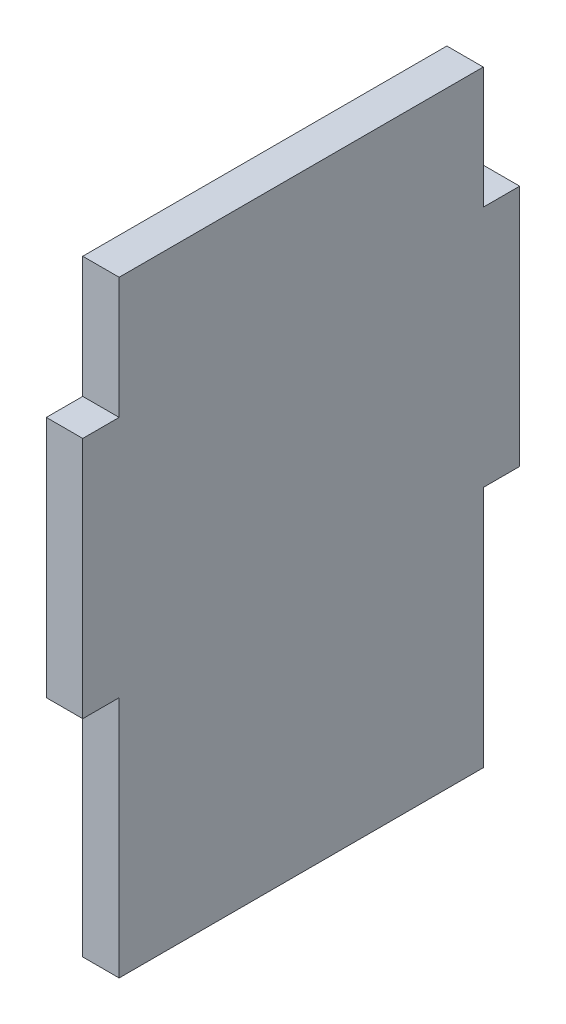
SolidWorks part; units mm, degrees
material "Acrilico TEC"
ref_plane "Front Plane" through (0, 0, 0) normal (0, 0, 1) x (1, 0, 0)
ref_plane "Top Plane" through (0, 0, 0) normal (0, 1, 0) x (1, 0, 0)
ref_plane "Right Plane" through (0, 0, 0) normal (1, 0, 0) x (0, 0, -1)
sketch "Sketch1" plane through (0, 0, 0) normal (1, 0, 0) x (0, 0, -1)
  line L0 (-15, 0) -> (15, 0)
  line L1 (15, 0) -> (15, 20)
  line L2 (15, 20) -> (18, 20)
  line L3 (18, 20) -> (18, 40)
  line L4 (18, 40) -> (15, 40)
  line L5 (15, 40) -> (15, 50)
  line L6 (15, 50) -> (-15, 50)
  line L7 (0, 50) -> (0, 0) construction
  line L8 (-15, 40) -> (-15, 50)
  line L9 (-18, 40) -> (-15, 40)
  line L10 (-18, 20) -> (-18, 40)
  line L11 (-15, 20) -> (-18, 20)
  line L12 (-15, 0) -> (-15, 20)
  dimension "D1" = 15
  dimension "D2" = 20
  dimension "D3" = 3
  dimension "D4" = 10
extrude "Boss-Extrude1" add sketch "Sketch1" along normal blind 3
ref_plane "Plane1" through (0, 0, 12) normal (0, 0, 1) x (1, 0, 0)
